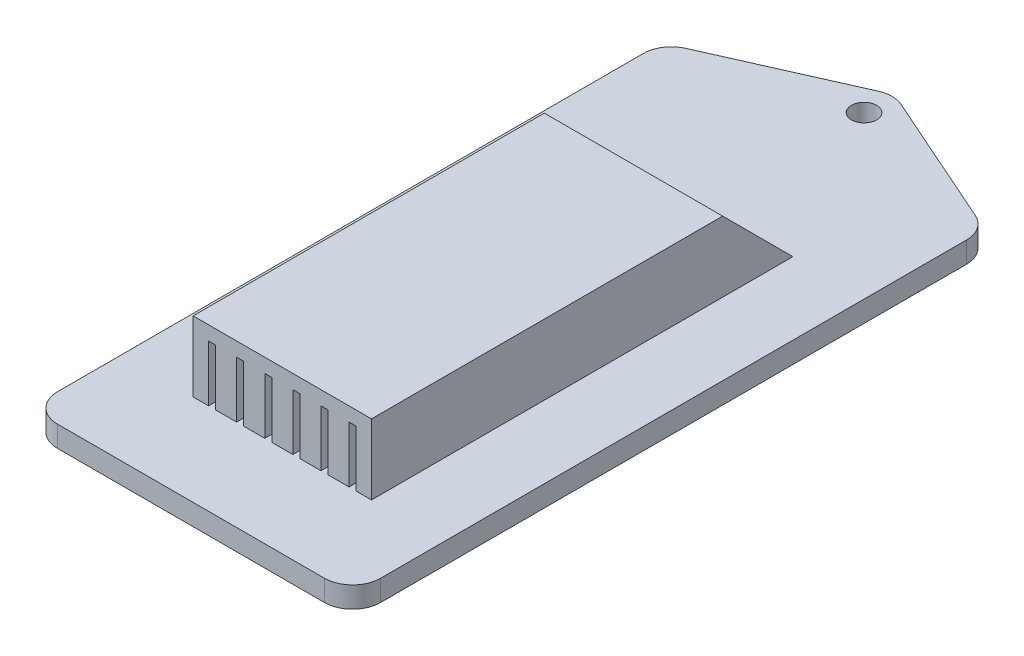
SolidWorks part; units mm, degrees
ref_plane "Front Plane" through (0, 0, 0) normal (0, 0, 1) x (1, 0, 0)
ref_plane "Top Plane" through (0, 0, 0) normal (0, 1, 0) x (1, 0, 0)
ref_plane "Right Plane" through (0, 0, 0) normal (1, 0, 0) x (0, 0, -1)
sketch "Sketch1" plane through (0, 0, 0) normal (0, 1, 0) x (1, 0, 0)
  line L0 (-115, 211.9911) -> (-115, -205)
  line L1 (-95, -225) -> (95, -225)
  line L2 (115, -205) -> (115, 211.9911)
  line L3 (103.108, 230.2738) -> (8.108, 272.4043)
  line L4 (-8.108, 272.4043) -> (-103.108, 230.2738)
  line L5 (0, 0) -> (0, -97.2724) construction
  arc A0 (8.108, 272.4043) -> (-8.108, 272.4043) centre (0, 254.1215) ccw
  arc A1 (-115, 211.9911) -> (-103.108, 230.2738) centre (-95, 211.9911) cw
  arc A2 (-95, -225) -> (-115, -205) centre (-95, -205) cw
  arc A3 (115, -205) -> (95, -225) centre (95, -205) cw
  arc A4 (115, 211.9911) -> (103.108, 230.2738) centre (95, 211.9911) ccw
  circle A5 centre (0, 254.1215) radius 9
  point P11 (0, 276)
  point P14 (-115, 225)
  point P17 (-115, -225)
  point P20 (115, -225)
  dimension "D5" = 20
  dimension "D6" = 20
  dimension "D7" = 20
  dimension "D8" = 20
  dimension "D9" = 20
  dimension "D10" = 18
  dimension "D1" = 51
  dimension "D2" = 450
  dimension "D3" = 230
  dimension "D4" = 225
extrude "Boss-Extrude1" add sketch "Sketch1" along normal blind 15
sketch "Sketch2" plane through (0, 0, 0) normal (1, 0, 0) x (0, 0, -1)
  line L0 (-160, 15) -> (-160, 65)
  line L1 (-205, 15) -> (211.9911, 15) construction
  line L2 (-160, 65) -> (90, 65)
  line L3 (90, 65) -> (140, 15)
  line L4 (-225, 15) -> (-225, 0) construction
  line L5 (-160, 15) -> (140, 15)
  dimension "D1" = 65
  dimension "D2" = 250
  dimension "D3" = 45
  dimension "D4" = 50
extrude "Boss-Extrude2" add sketch "Sketch2" along normal blind 63.5 and the other way blind 63.5
sketch "Sketch4" plane through (0, 0, 0) normal (0, 0, 1) x (1, 0, 0)
  line L0 (52.5, 15) -> (52.5, 55)
  line L1 (-63.5, 15) -> (63.5, 15) construction
  line L2 (52.5, 55) -> (47.5, 55)
  line L3 (47.5, 55) -> (47.5, 15)
  line L4 (103.108, 15) -> (8.108, 15) construction
  line L5 (47.5, 15) -> (52.5, 15)
  line L6 (63.5, 15) -> (63.5, 65) construction
  line L7 (27.5, 15) -> (32.5, 15)
  line L8 (32.5, 15) -> (32.5, 55)
  line L9 (32.5, 55) -> (27.5, 55)
  line L10 (27.5, 55) -> (27.5, 15)
  line L11 (7.5, 15) -> (12.5, 15)
  line L12 (12.5, 15) -> (12.5, 55)
  line L13 (12.5, 55) -> (7.5, 55)
  line L14 (7.5, 55) -> (7.5, 15)
  line L15 (-12.5, 15) -> (-7.5, 15)
  line L16 (-7.5, 15) -> (-7.5, 55)
  line L17 (-7.5, 55) -> (-12.5, 55)
  line L18 (-12.5, 55) -> (-12.5, 15)
  line L19 (-32.5, 15) -> (-27.5, 15)
  line L20 (-27.5, 15) -> (-27.5, 55)
  line L21 (-27.5, 55) -> (-32.5, 55)
  line L22 (-32.5, 55) -> (-32.5, 15)
  line L23 (-52.5, 15) -> (-47.5, 15)
  line L24 (-47.5, 15) -> (-47.5, 55)
  line L25 (-47.5, 55) -> (-52.5, 55)
  line L26 (-52.5, 55) -> (-52.5, 15)
  dimension "D1" = 5
  dimension "D2" = 40
  dimension "D3" = 11
  dimension "D5" = 20
  dimension "D4" = 6
extrude "Cut-Extrude1" cut sketch "Sketch4" against normal blind 200 and the other way blind 200 contours L25 L26 L23 L24 | L0 L2 L3 L5 | L10 L7 L8 L9 | L14 L11 L12 L13 | L18 L15 L16 L17 | L20 L21 L22 L19
